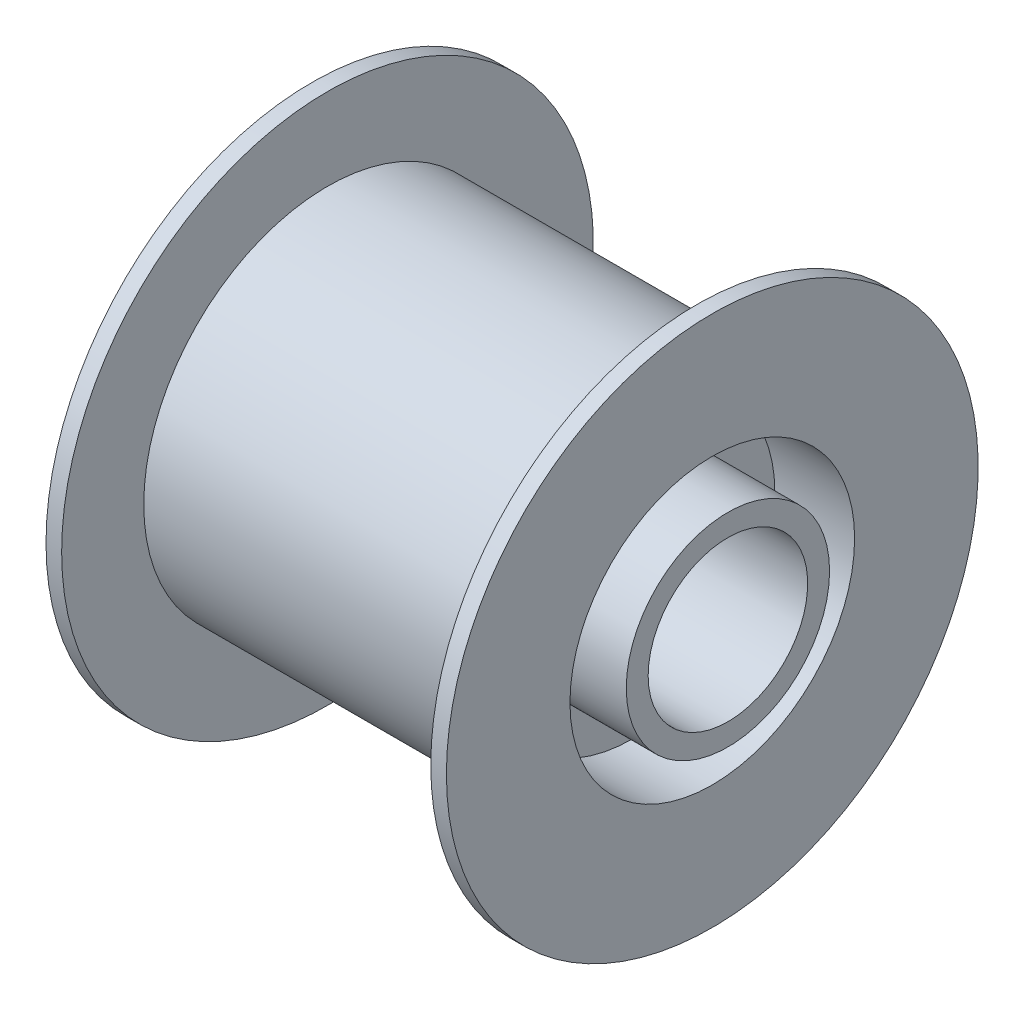
SolidWorks part; units mm, degrees
material "SUS304"
ref_plane "Front Plane" through (0, 0, 0) normal (0, 0, 1) x (1, 0, 0)
ref_plane "Top Plane" through (0, 0, 0) normal (0, 1, 0) x (1, 0, 0)
ref_plane "Right Plane" through (0, 0, 0) normal (1, 0, 0) x (0, 0, -1)
ref_plane "Plane1" through (13.8, 0, 0) normal (1, 0, 0) x (0, 0, -1)
sketch "Sketch1" plane through (0, 0, 0) normal (0, 0, 1) x (1, 0, 0)
  line L0 (0, 0) -> (27.6, 0) construction
  line L1 (0, 6.5) -> (0, 5.1)
  line L2 (0, 5.1) -> (27.6, 5.1)
  line L3 (27.6, 5.1) -> (27.6, 6.5)
  line L4 (27.6, 6.5) -> (21.5, 6.5)
  line L5 (6.1, 6.5) -> (6.1, 9.1)
  line L6 (21.5, 6.5) -> (21.5, 9.1)
  line L7 (6.1, 6.5) -> (0, 6.5)
  line L8 (1, 9.1) -> (1, 17)
  line L9 (1, 17) -> (2, 17)
  line L10 (2, 17) -> (2, 11.75)
  line L11 (2, 11.75) -> (25.6, 11.75)
  line L12 (25.6, 11.75) -> (25.6, 17)
  line L13 (25.6, 17) -> (26.6, 17)
  line L14 (26.6, 17) -> (26.6, 9.1)
  line L15 (0, 0) -> (0, 17) construction
  line L16 (0, 17) -> (1, 17) construction
  line L17 (27.6, 6.5) -> (27.6, 17) construction
  line L18 (27.6, 17) -> (26.6, 17) construction
  line L19 (21.5, 9.1) -> (26.6, 9.1)
  line L20 (1, 9.1) -> (6.1, 9.1)
  dimension "L" = 27.6
  dimension "D1." = 13
  dimension "V" = 10.2
  dimension "MSM_4" = 6.1
  dimension "D" = 34
  dimension "L_s" = 25.6
  dimension "MSM_2" = 2.6
  dimension "MSM_3" = 1
  dimension "MSM_1" = 23.5
revolve "Revolve1" add sketch "Sketch1" angle 360 about L0
equation "\"FIX_1@Plane1\"= \"L@Sketch1\" * 0.5"
